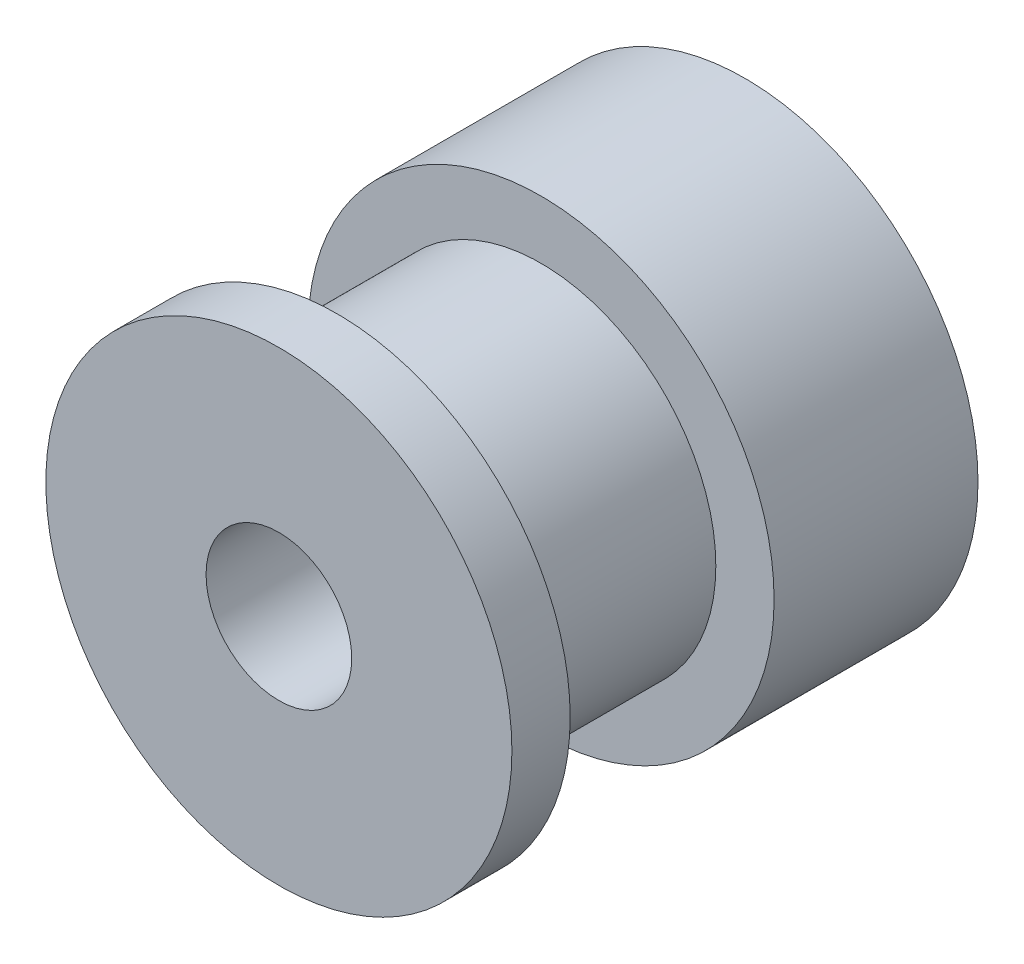
SolidWorks part; units mm, degrees
ref_plane "前视基准面" through (0, 0, 0) normal (0, 0, 1) x (1, 0, 0)
ref_plane "上视基准面" through (0, 0, 0) normal (0, 1, 0) x (1, 0, 0)
ref_plane "右视基准面" through (0, 0, 0) normal (1, 0, 0) x (0, 0, -1)
other "Configuration Table"
sketch "草图1" plane through (0, 0, 0) normal (0, 0, 1) x (1, 0, 0)
  circle A0 centre (0, 0) radius 8
  dimension "D1" = 16
extrude "凸台-拉伸1" add sketch "草图1" along normal blind 7
sketch "草图2" plane through (0, 0, 7) normal (0, 0, 1) x (1, 0, 0)
  circle A0 centre (0, 0) radius 6
  dimension "D1" = 12
extrude "凸台-拉伸2" add sketch "草图2" along normal blind 7
sketch "草图3" plane through (0, 0, 14) normal (0, 0, 1) x (1, 0, 0)
  circle A0 centre (0, 0) radius 8
extrude "凸台-拉伸3" add sketch "草图3" along normal blind 2
sketch "草图4" plane through (0, 0, 0) normal (0, 0, -1) x (-1, 0, 0)
  circle A0 centre (0, 0) radius 2.5
  dimension "D1" = 5
extrude "切除-拉伸1" cut sketch "草图4" against normal up to surface (16 mm away) up to face at (8, 0, 16)
